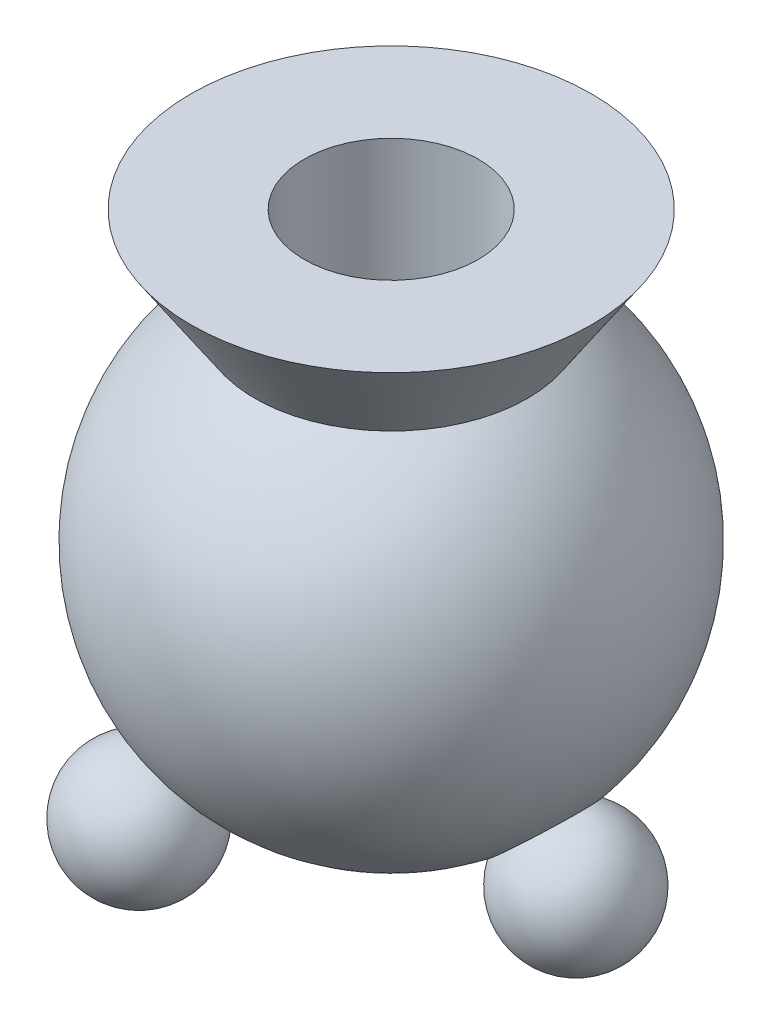
SolidWorks part; units mm, degrees
ref_plane "Front Plane" through (0, 0, 0) normal (0, 0, 1) x (1, 0, 0)
ref_plane "Top Plane" through (0, 0, 0) normal (0, 1, 0) x (1, 0, 0)
ref_plane "Right Plane" through (0, 0, 0) normal (1, 0, 0) x (0, 0, -1)
sketch "Sketch1" plane through (0, 0, 0) normal (0, 0, 1) x (1, 0, 0)
  line L0 (0, 0) -> (0, 40)
  line L1 (10, 60) -> (23, 60)
  line L2 (23, 60) -> (15.6525, 49)
  line L6 (0, 40) -> (10, 40)
  line L7 (10, 60) -> (10, 40)
  arc A0 (15.6525, 49) -> (0, 0) centre (0, 27) cw
  dimension "D1" = 27
  dimension "D2" = 13
  dimension "D3" = 56.259
  dimension "D4" = 11
  dimension "D5" = 10
  dimension "D6" = 20
revolve "Revolve1" add sketch "Sketch1" angle 360 about L0
sketch "Sketch2" plane through (0, 0, 0) normal (0, 0, 1) x (1, 0, 0)
  line L0 (15.6525, 49) -> (-15.6525, 49) construction
  line L1 (0, 0) -> (0, 49) construction
  line L3 (15.6525, 49) -> (-15.6525, 49) construction
  line L5 (15.9099, 8.5901) -> (26.5165, -2.0165)
  line L6 (0, 24.5) -> (21.2132, 3.2868) construction
  arc A2 (26.5165, -2.0165) -> (15.9099, 8.5901) centre (21.2132, 3.2868) ccw
  point P7 (0, 47.7879)
  point P10 (0, 49)
  dimension "D2" = 15
  dimension "D1" = 45
  dimension "D3" = 30
revolve "Revolve2" add sketch "Sketch2" angle 360 about L5
pattern_circular "CirPattern1" count 3 over 360 about axis through (0, 0, 0) along (0, 1, 0) of "Revolve2"
